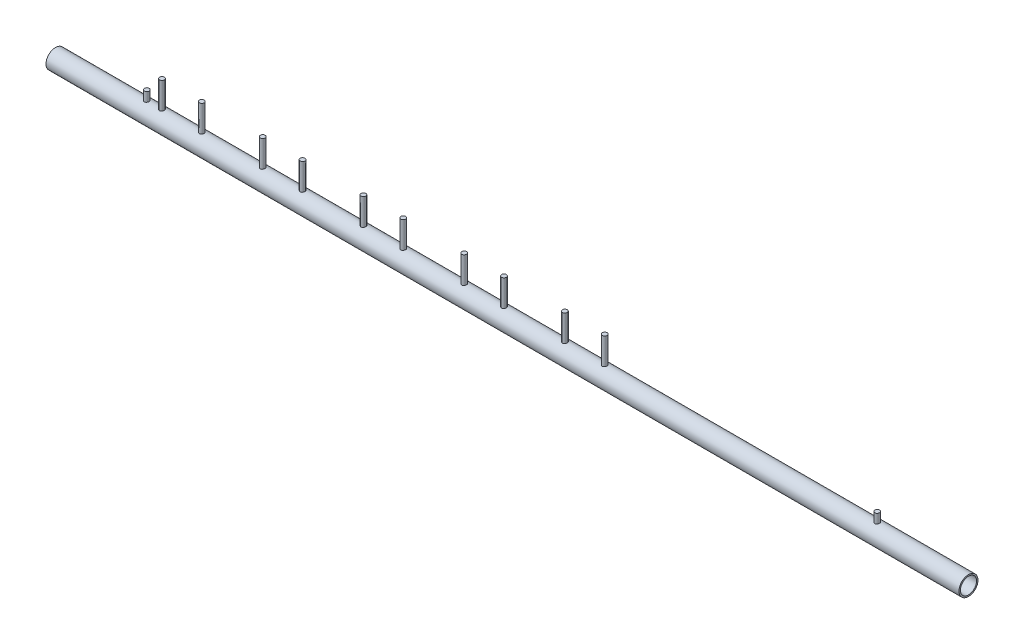
SolidWorks part; units mm, degrees
ref_plane "Front Plane" through (0, 0, 0) normal (0, 0, 1) x (1, 0, 0)
ref_plane "Top Plane" through (0, 0, 0) normal (0, 1, 0) x (1, 0, 0)
ref_plane "Right Plane" through (0, 0, 0) normal (1, 0, 0) x (0, 0, -1)
sketch "Sketch2" plane through (0, 0, 0) normal (1, 0, 0) x (0, 0, -1)
  circle A0 centre (0, 0) radius 15.875
  circle A1 centre (0, 0) radius 13.462
  dimension "D1" = 31.75
  dimension "D2" = 2.413
extrude "Boss-Extrude2" add sketch "Sketch2" along normal blind 1524
sketch "Sketch3" plane through (0, 0, 0) normal (0, 1, 0) x (1, 0, 0)
  line L0 (0, 0) -> (152.4, 0) construction
  line L1 (152.4, 0) -> (1371.6, 0) construction
  line L2 (1524, -15.875) -> (1524, 15.875) construction
  circle A19 centre (152.4, 0) radius 4
  circle A23 centre (1371.6, 0) radius 4
  dimension "D1" = 152.4
  dimension "D4" = 8
  dimension "D3" = 8
  dimension "D2" = 152.4
extrude "Boss-Extrude3" add sketch "Sketch3" along normal blind 19.05 from offset 12
sketch "Sketch4" plane through (0, 0, 0) normal (0, 1, 0) x (1, 0, 0)
  line L0 (0, 0) -> (152.4, 0) construction
  line L1 (152.4, 0) -> (177.8, 0) construction
  line L2 (177.8, 0) -> (244.32, 0) construction
  circle A0 centre (244.32, 0) radius 4
  circle A1 centre (177.8, 0) radius 4
  circle A2 centre (345.92, 0) radius 4
  circle A3 centre (412.44, 0) radius 4
  circle A4 centre (514.04, 0) radius 4
  circle A5 centre (580.56, 0) radius 4
  circle A6 centre (682.16, 0) radius 4
  circle A7 centre (748.68, 0) radius 4
  circle A8 centre (850.28, 0) radius 4
  circle A9 centre (916.8, 0) radius 4
  dimension "D2" = 8
  dimension "D3" = 66.52
  dimension "D4" = 8
  dimension "D1" = 25.4
  dimension "D5" = 101.6
extrude "Boss-Extrude4" add sketch "Sketch4" along normal blind 60
